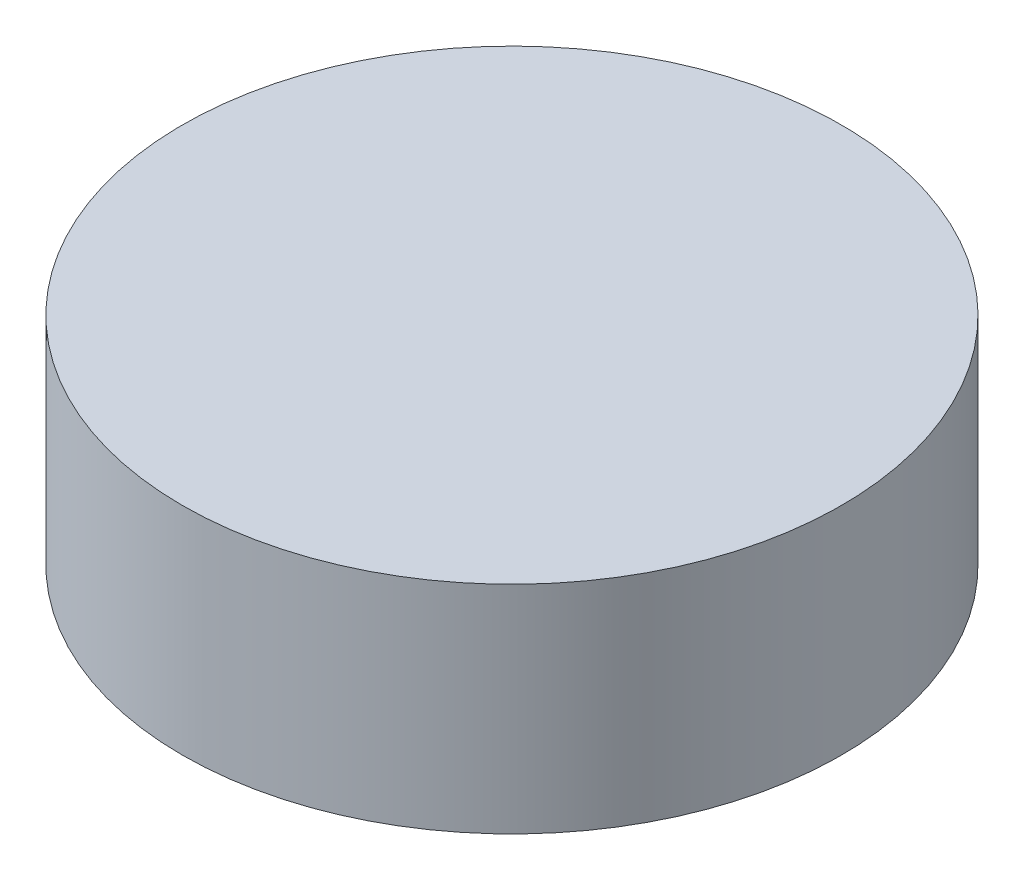
SolidWorks part; units mm, degrees
ref_plane "Front Plane" through (0, 0, 0) normal (0, 0, 1) x (1, 0, 0)
ref_plane "Top Plane" through (0, 0, 0) normal (0, 1, 0) x (1, 0, 0)
ref_plane "Right Plane" through (0, 0, 0) normal (1, 0, 0) x (0, 0, -1)
sketch "Sketch1" plane through (0, 0, 0) normal (0, 1, 0) x (1, 0, 0)
  circle A0 centre (0, 0) radius 76.2
extrude "Boss-Extrude1" add sketch "Sketch1" along normal blind 50 contours A0
